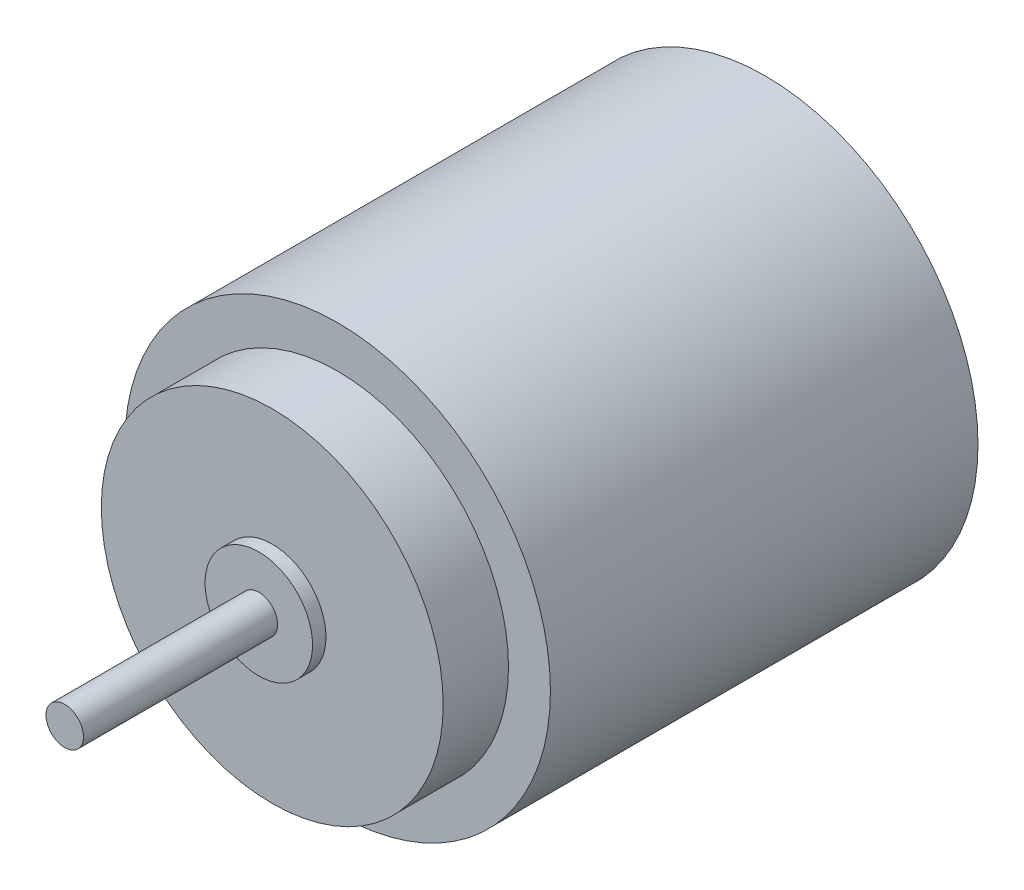
SolidWorks part; units mm, degrees
ref_plane "Front Plane" through (0, 0, 0) normal (0, 0, 1) x (1, 0, 0)
ref_plane "Top Plane" through (0, 0, 0) normal (0, 1, 0) x (1, 0, 0)
ref_plane "Right Plane" through (0, 0, 0) normal (1, 0, 0) x (0, 0, -1)
sketch "Sketch1" plane through (0, 0, 0) normal (0, 0, 1) x (1, 0, 0)
  circle A0 centre (0, 0) radius 11.6713
  dimension "D1" = 23.3426
extrude "Boss-Extrude1" add sketch "Sketch1" along normal blind 23.4442 contours A0
sketch "Sketch4" plane through (0, 0, 23.4442) normal (0, 0, 1) x (1, 0, 0)
  circle A0 centre (0, 0) radius 9.3726
  dimension "D1" = 18.7452
extrude "Boss-Extrude3" add sketch "Sketch4" along normal blind 3.5814
sketch "Sketch5" plane through (0, 0, 27.0256) normal (0, 0, 1) x (1, 0, 0)
  circle A0 centre (0, 0) radius 2.9464
  dimension "D1" = 5.8928
extrude "Boss-Extrude4" add sketch "Sketch5" along normal blind 0.7366
sketch "Sketch2" plane through (0, 0, 27.7622) normal (0, 0, 1) x (1, 0, 0)
  circle A0 centre (0, 0) radius 1.0287
  dimension "D1" = 2.0574
extrude "Boss-Extrude2" add sketch "Sketch2" along normal blind 10.6426
equation "\"MotorLength\"=0.923"
equation "\"MotorDiameter\"=0.919"
equation "\"ShaftLength\"=0.419"
equation "\"ShaftDiameter\"= 0.081"
equation "\"D1@Sketch1\"= \"MotorDiameter\""
equation "\"D1@Boss-Extrude1\"= \"MotorLength\""
equation "\"D1@Sketch2\"= \"ShaftDiameter\""
equation "\"D1@Boss-Extrude2\"= \"ShaftLength\""
equation "\"midShaftDiameter\"= 0.23200000in"
equation "\"D1@Sketch5\"=\"midShaftDiameter\""
